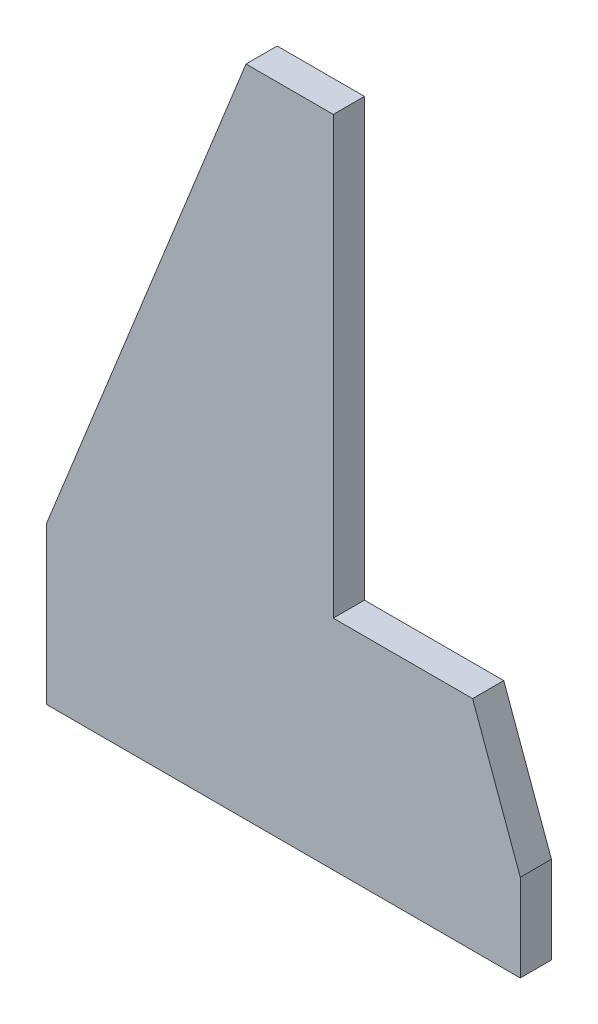
SolidWorks part; units mm, degrees
ref_plane "Ön Düzlem" through (0, 0, 0) normal (0, 0, 1) x (1, 0, 0)
ref_plane "Üst Düzlem" through (0, 0, 0) normal (0, 1, 0) x (1, 0, 0)
ref_plane "Sağ Düzlem" through (0, 0, 0) normal (1, 0, 0) x (0, 0, -1)
sketch "Çizim1" plane through (0, 0, 0) normal (0, 0, 1) x (1, 0, 0)
  line L0 (-210, 28) -> (-210, 0)
  line L1 (-210, 0) -> (0, 0)
  line L2 (0, 0) -> (0, 28)
  line L3 (0, 28) -> (-15.3, 70)
  line L4 (-15.3, 70) -> (-60, 70)
  line L5 (-60, 70) -> (-60, 210)
  line L6 (-60, 210) -> (-88, 210)
  line L7 (-88, 210) -> (-210, 28)
  point P2 (-3.3109, 80)
  point P10 (-17.3338, 60)
  point P11 (-17.0703, 70)
  dimension "D1" = 28
  dimension "D2" = 28
  dimension "D3" = 210
  dimension "D4" = 210
  dimension "D5" = 28
  dimension "D6" = 140
  dimension "D7" = 150
extrude "Yükseklik-Ekstrüzyon1" add sketch "Çizim1" along normal blind 10
sketch "Sketch1" plane through (0, 0, 0) normal (0, 0, -1) x (-1, 0, 0)
  line L0 (210, 28) -> (210, 0) construction
  line L1 (152, 150.4691) -> (245.1766, 150.4691)
  line L2 (152, 50.3471) -> (152, -14.3388)
  line L3 (152, -14.3388) -> (245.1766, -14.3388)
  line L4 (245.1766, 150.4691) -> (245.1766, -14.3388)
  line L5 (88, 210) -> (152, 50.3471)
  line L6 (88, 210) -> (210, 28) construction
  line L7 (152, 150.4691) -> (152, 210)
  line L8 (152, 210) -> (88, 210)
  point P10 (152, 80.2276)
  point P12 (88, 210)
  point P14 (152, 61.7589)
  point P15 (152, 50.3471)
  dimension "D1" = 58
extrude "Cut-Extrude1" cut sketch "Sketch1" against normal blind 10
